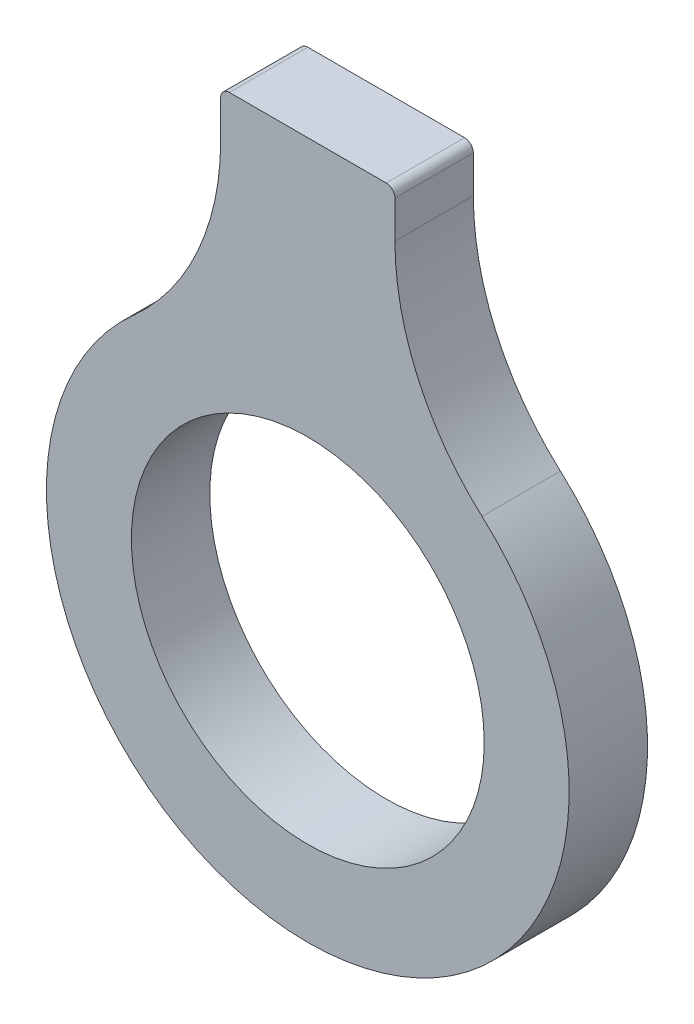
SolidWorks part; units mm, degrees
ref_plane "前视基准面" through (0, 0, 0) normal (0, 0, 1) x (1, 0, 0)
ref_plane "上视基准面" through (0, 0, 0) normal (0, 1, 0) x (1, 0, 0)
ref_plane "右视基准面" through (0, 0, 0) normal (1, 0, 0) x (0, 0, -1)
sketch "草图1" plane through (0, 0, 0) normal (0, 0, 1) x (1, 0, 0)
  line L0 (-2, 8.9443) -> (-2, 9.8)
  line L1 (2, 8.9443) -> (2, 9.8)
  line L2 (-1.8, 10) -> (1.8, 10)
  arc A0 (-4, 4.4721) -> (4, 4.4721) centre (0, 0) ccw
  arc A1 (-4, 4.4721) -> (-2, 8.9443) centre (-8, 8.9443) ccw
  arc A2 (2, 8.9443) -> (4, 4.4721) centre (8, 8.9443) ccw
  arc A3 (2, 9.8) -> (1.8, 10) centre (1.8, 9.8) ccw
  arc A4 (-1.8, 10) -> (-2, 9.8) centre (-1.8, 9.8) ccw
extrude "凸台-拉伸1" add sketch "草图1" against normal blind 1.8
sketch "草图2" plane through (0, 0, 0) normal (0, 0, 1) x (1, 0, 0)
  circle A0 centre (0, 0) radius 4.05
extrude "切除-拉伸1" cut sketch "草图2" against normal blind 1.8
